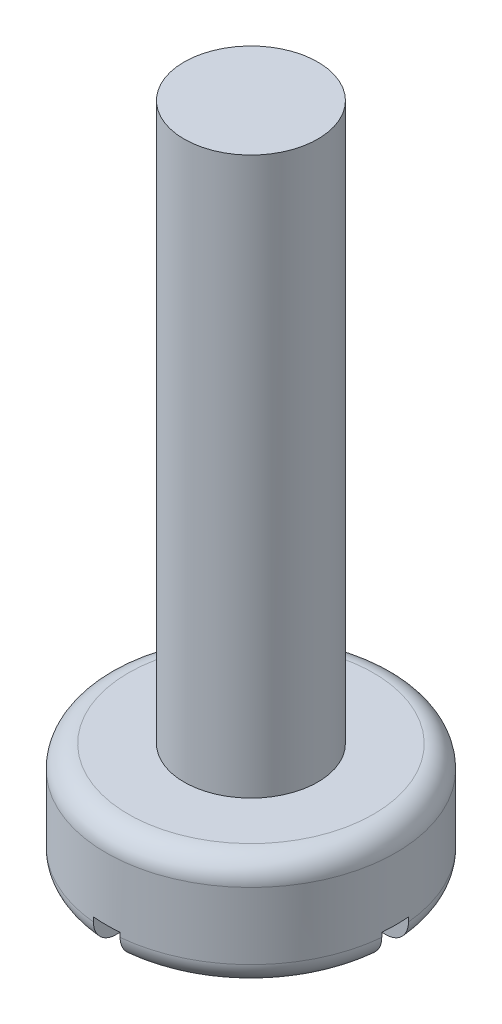
SolidWorks part; units mm, degrees
material "Plain Carbon Steel"
ref_plane "Front Plane" through (0, 0, 0) normal (0, 0, 1) x (1, 0, 0)
ref_plane "Top Plane" through (0, 0, 0) normal (0, 1, 0) x (1, 0, 0)
ref_plane "Right Plane" through (0, 0, 0) normal (1, 0, 0) x (0, 0, -1)
sketch "Sketch1" plane through (0, 0, 0) normal (0, 1, 0) x (1, 0, 0)
  circle A0 centre (0, 0) radius 3
  dimension "D1" = 6
extrude "Boss-Extrude1" add sketch "Sketch1" along normal blind 25
cosmetic thread "Cosmetic Thread1" parameters "D1"=30, "D2"=0.3
sketch "Sketch2" plane through (0, 0, 0) normal (0, 0, 1) x (1, 0, 0)
  line L0 (0, 0) -> (0, -5)
  line L1 (-5.5, 0) -> (0, 0)
  line L2 (-6.5, -1) -> (-6.5, -4)
  line L3 (-5.5, -5) -> (0, -5)
  arc A2 (-6.5, -4) -> (-5.5, -5) centre (-5.5, -4) ccw
  arc A3 (-5.5, 0) -> (-6.5, -1) centre (-5.5, -1) ccw
  point P9 (6.5, -5)
  point P12 (-6.5, -5)
  point P15 (-6.5, 0)
  dimension "D1" = 13
  dimension "D2" = 6.5
  dimension "D3" = 5
  dimension "D4" = 0
revolve "Revolve1" add sketch "Sketch2" angle 360 about L0
sketch "Sketch3" plane through (0, -5, 0) normal (0, -1, 0) x (1, 0, 0)
  line L0 (0, 8.3754) -> (0, -7.9305) construction
  line L1 (0.6, 8.3754) -> (-0.6, 8.3754)
  line L2 (0.6, 8.3754) -> (0.6, 0.8)
  line L3 (0.6, -7.9305) -> (-0.6, -7.9305)
  line L4 (-0.6, 8.3754) -> (-0.6, 0.8)
  line L5 (-7.3941, -0.6) -> (-0.8, -0.6)
  line L6 (-7.3941, -0.6) -> (-7.3941, 0.6)
  line L7 (-7.3941, 0.6) -> (-0.8, 0.6)
  line L8 (8.8402, -0.6) -> (8.8402, 0.6)
  line L9 (8.8402, 0) -> (-7.3941, 0) construction
  line L10 (0.8, 0.6) -> (8.8402, 0.6)
  line L11 (-0.6, -0.8) -> (-0.6, -7.9305)
  line L12 (0.8, -0.6) -> (8.8402, -0.6)
  line L13 (0.6, -0.8) -> (0.6, -7.9305)
  line L14 (0.6, 0.8) -> (0.8, 0.6)
  line L15 (0.8, -0.6) -> (0.6, -0.8)
  line L16 (-0.8, -0.6) -> (-0.6, -0.8)
  line L17 (-0.8, 0.6) -> (-0.6, 0.8)
  point P12 (0, 0)
  point P13 (-0.6, 0.6)
  point P16 (-0.6, -0.6)
  point P17 (0.6, 0.6)
  point P18 (0.6, -0.6)
  dimension "D1" = 1.2
  dimension "D2" = 1.2
extrude "Cut-Extrude1" cut sketch "Sketch3" against normal blind 1.2
